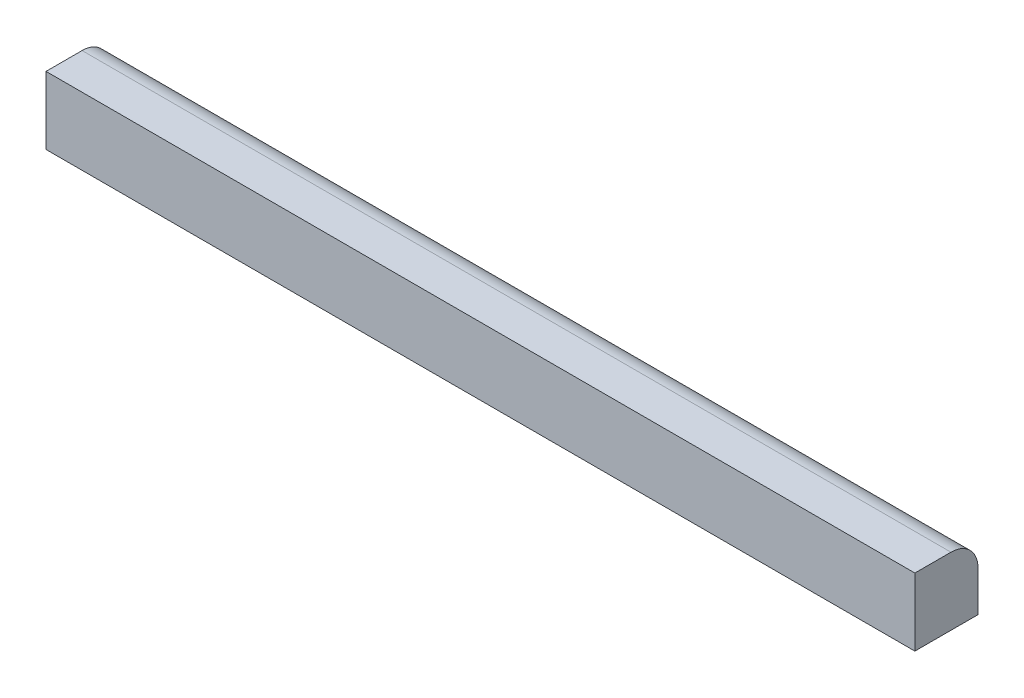
SolidWorks part; units mm, degrees
ref_plane "前视基准面" through (0, 0, 0) normal (0, 0, 1) x (1, 0, 0)
ref_plane "上视基准面" through (0, 0, 0) normal (0, 1, 0) x (1, 0, 0)
ref_plane "右视基准面" through (0, 0, 0) normal (1, 0, 0) x (0, 0, -1)
sketch "草图1" plane through (0, 0, 0) normal (0, 0, 1) x (1, 0, 0)
  line L1 (-144.5, -11.25) -> (144.5, -11.25)
  line L2 (-144.5, -11.25) -> (-144.5, 11.25)
  line L3 (-144.5, 11.25) -> (144.5, 11.25)
  line L4 (144.5, -11.25) -> (144.5, 11.25)
  line L5 (-144.5, -11.25) -> (144.5, 11.25) construction
  line L6 (-144.5, 11.25) -> (144.5, -11.25) construction
  point P0 (0, 0)
  dimension "D1" = 289
  dimension "D2" = 22.5
extrude "凸台-拉伸1" add sketch "草图1" along normal blind 21
fillet "圆角1" radius 9 1 edges at (0, 11.25, 0)
